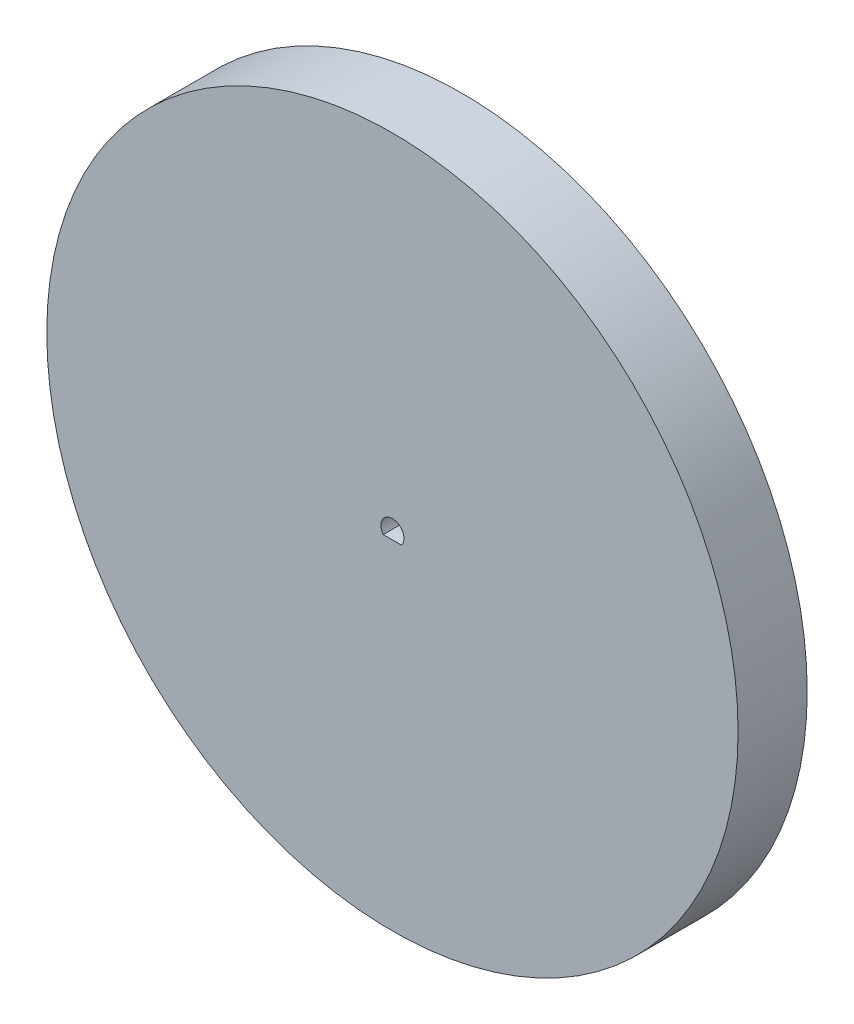
SolidWorks part; units mm, degrees
ref_plane "Alzado" through (0, 0, 0) normal (0, 0, 1) x (1, 0, 0)
ref_plane "Planta" through (0, 0, 0) normal (0, 1, 0) x (1, 0, 0)
ref_plane "Vista lateral" through (0, 0, 0) normal (1, 0, 0) x (0, 0, -1)
sketch "Croquis1" plane through (0, 0, 0) normal (0, 0, 1) x (1, 0, 0)
  line L0 (0, 2.5) -> (0, -1.5)
  line L1 (0, -1.5) -> (-2, -1.5)
  line L2 (2, -1.5) -> (0, -1.5)
  circle A0 centre (0, 0) radius 75
  circle A1 centre (0, 0) radius 2.5
  dimension "D1" = 150
  dimension "D2" = 5
  dimension "D3" = 4
extrude "Saliente-Extruir1" add sketch "Croquis1" along normal blind 15 contours A0 A1 | L1 A1 L2
